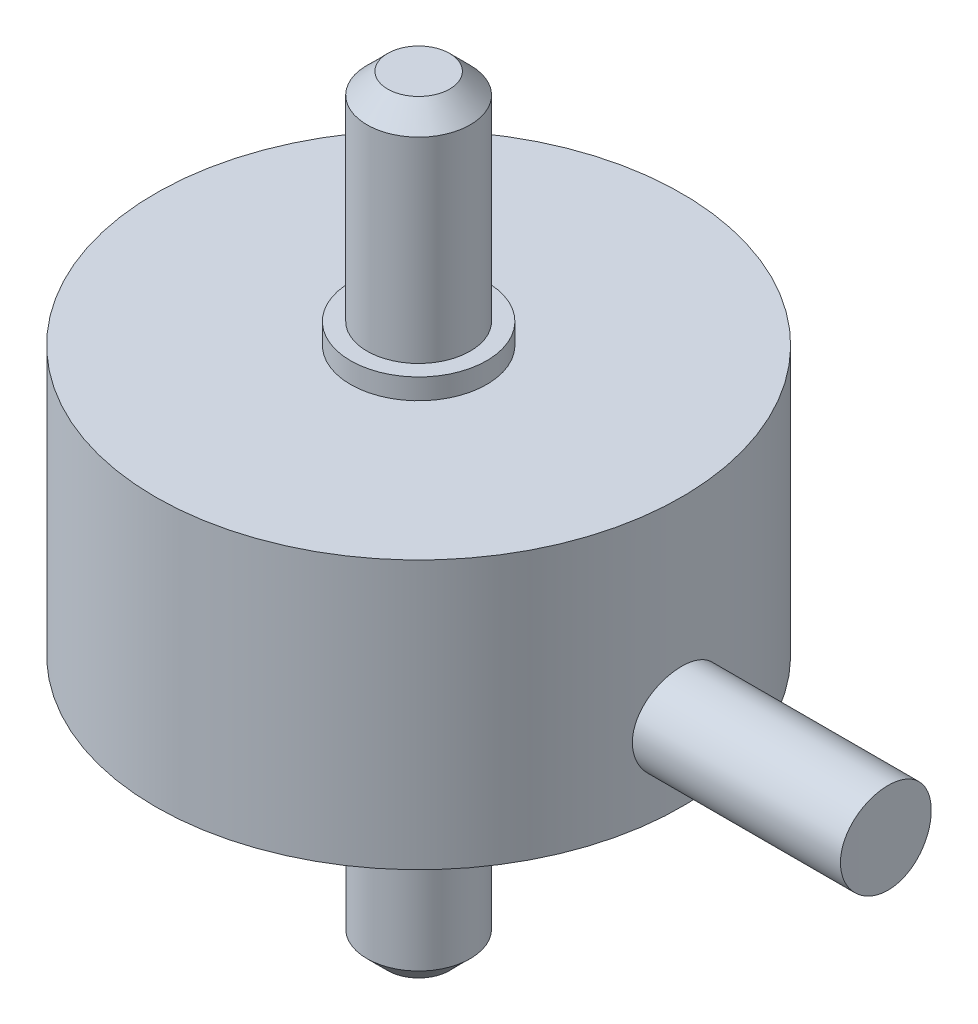
SolidWorks part; units mm, degrees
ref_plane "Front Plane" through (0, 0, 0) normal (0, 0, 1) x (1, 0, 0)
ref_plane "Top Plane" through (0, 0, 0) normal (0, 1, 0) x (1, 0, 0)
ref_plane "Right Plane" through (0, 0, 0) normal (1, 0, 0) x (0, 0, -1)
sketch "Sketch1" plane through (0, 0, 0) normal (0, 1, 0) x (1, 0, 0)
  circle A0 centre (0, 0) radius 12.75
  dimension "D1" = 25.5
extrude "Boss-Extrude1" add sketch "Sketch1" along normal blind 13
sketch "Sketch2" plane through (0, 13, 0) normal (0, 1, 0) x (1, 0, 0)
  circle A0 centre (0, 0) radius 3.3
  dimension "D1" = 6.6
extrude "Boss-Extrude2" add sketch "Sketch2" along normal blind 1
sketch "Sketch3" plane through (0, 14, 0) normal (0, 1, 0) x (1, 0, 0)
  circle A0 centre (0, 0) radius 2.5
  dimension "D1" = 5
extrude "Boss-Extrude3" add sketch "Sketch3" along normal blind 10.5
sketch "Sketch4" plane through (0, 0, 0) normal (0, -1, 0) x (1, 0, 0)
  circle A0 centre (0, 0) radius 5
  dimension "D1" = 10
extrude "Boss-Extrude4" add sketch "Sketch4" along normal blind 2
sketch "Sketch5" plane through (0, -2, 0) normal (0, -1, 0) x (1, 0, 0)
  circle A0 centre (0, 0) radius 2.5
  dimension "D1" = 5
extrude "Boss-Extrude5" add sketch "Sketch5" along normal blind 10.5
chamfer "Chamfer1" distance 1 angle 45 2 edges at (0, 24.5, 2.5) (0, -12.5, -2.5)
sketch "Sketch6" plane through (0, 0, 0) normal (1, 0, 0) x (0, 0, -1)
  line L0 (0, 3.7) -> (0, 0) construction
  line L1 (0, 1.5) -> (8.9681, 1.5) construction
  line L2 (-12.75, 0) -> (12.75, 0) construction
  circle A0 centre (0, 3.7) radius 2.2
  dimension "D1" = 4.4
  dimension "D2" = 1.5
extrude "Boss-Extrude6" add sketch "Sketch6" along normal offset from surface (22.6434 mm away) 10
